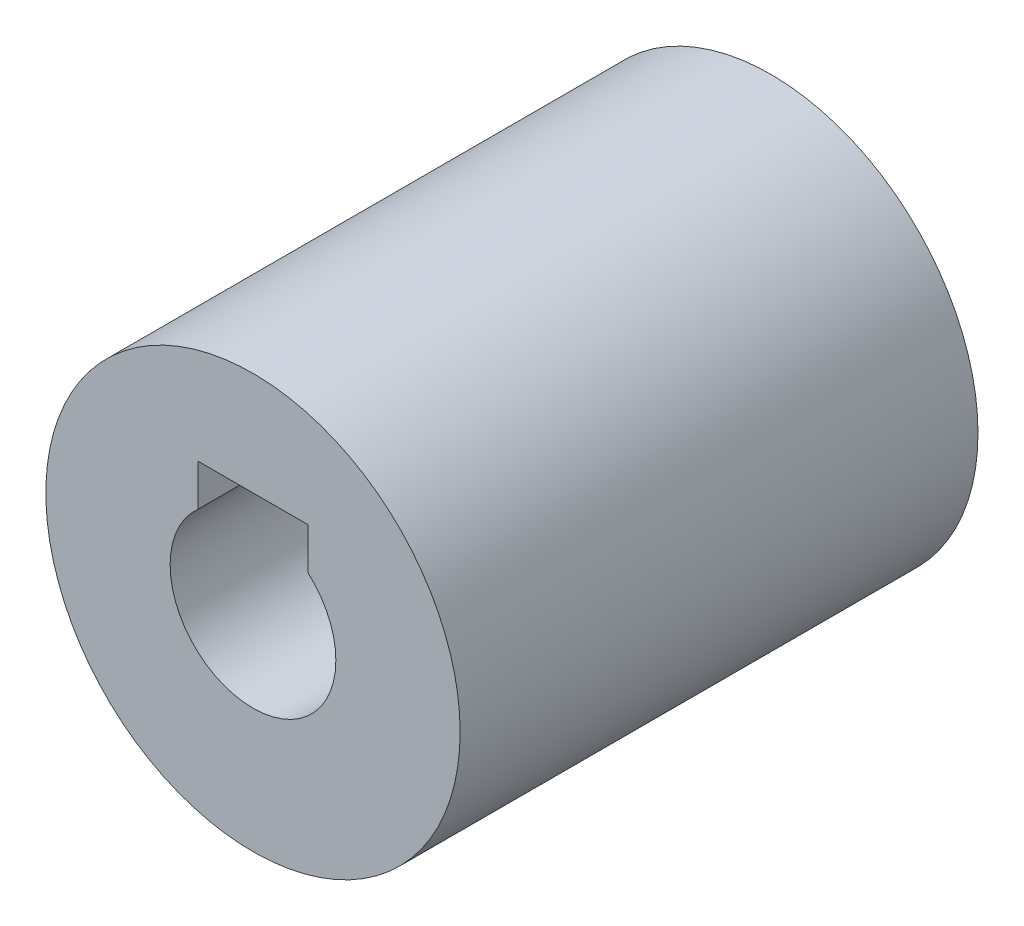
SolidWorks part; units mm, degrees
ref_plane "Front Plane" through (0, 0, 0) normal (0, 0, 1) x (1, 0, 0)
ref_plane "Top Plane" through (0, 0, 0) normal (0, 1, 0) x (1, 0, 0)
ref_plane "Right Plane" through (0, 0, 0) normal (1, 0, 0) x (0, 0, -1)
sketch "Sketch1" plane through (0, 0, 0) normal (0, 0, 1) x (1, 0, 0)
  line L0 (0, 4) -> (0, -4) construction
  line L1 (-2.6458, 3) -> (2.6458, 3)
  line L2 (-2.6458, 3) -> (-2.6458, 5)
  line L3 (-2.6458, 5) -> (2.6458, 5)
  line L4 (2.6458, 3) -> (2.6458, 5)
  circle A0 centre (0, 0) radius 10
  circle A1 centre (0, 0) radius 4
  dimension "D1" = 1
  dimension "D2" = 8
  dimension "D3" = 20
  dimension "D4" = 2
extrude "Boss-Extrude1" add sketch "Sketch1" along normal blind 25 contours A0 A1 L2 L3 L4
